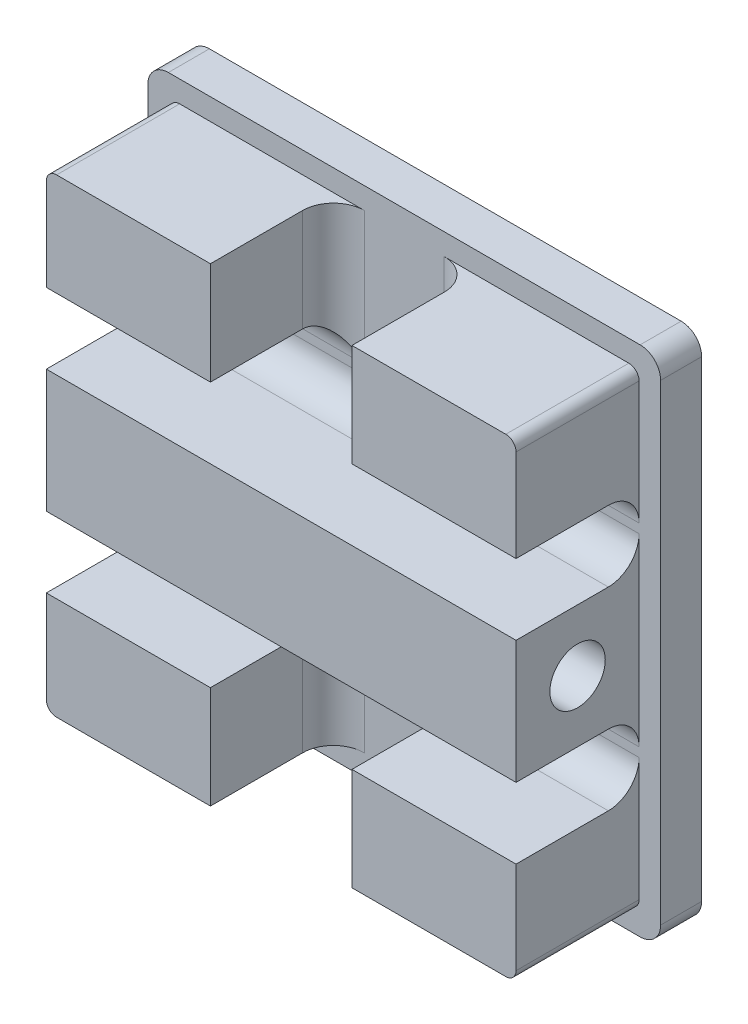
SolidWorks part; units mm, degrees
material "PLA"
ref_plane "前视基准面" through (0, 0, 0) normal (0, 0, 1) x (1, 0, 0)
ref_plane "上视基准面" through (0, 0, 0) normal (0, 1, 0) x (1, 0, 0)
ref_plane "右视基准面" through (0, 0, 0) normal (1, 0, 0) x (0, 0, -1)
sketch "草图1" plane through (0, 0, 0) normal (0, 0, 1) x (1, 0, 0)
  line L1 (12.5, -12.5) -> (-12.5, -12.5)
  line L2 (12.5, -12.5) -> (12.5, 12.5)
  line L3 (12.5, 12.5) -> (-12.5, 12.5)
  line L4 (-12.5, -12.5) -> (-12.5, 12.5)
  line L5 (12.5, -12.5) -> (-12.5, 12.5) construction
  line L6 (12.5, 12.5) -> (-12.5, -12.5) construction
  point P0 (0, 0)
  dimension "D1" = 25
extrude "凸台-拉伸1" add sketch "草图1" along normal blind 2
sketch "草图2" plane through (0, 0, 2) normal (0, 0, 1) x (1, 0, 0)
  line L1 (-11.45, 11.45) -> (11.45, 11.45)
  line L2 (-11.45, 11.45) -> (-11.45, -11.45)
  line L3 (-11.45, -11.45) -> (11.45, -11.45)
  line L4 (11.45, 11.45) -> (11.45, -11.45)
  line L5 (-11.45, 11.45) -> (11.45, -11.45) construction
  line L6 (-11.45, -11.45) -> (11.45, 11.45) construction
  point P0 (0, 0)
  dimension "D1" = 22.9
extrude "凸台-拉伸2" add sketch "草图2" along normal blind 6
fillet "圆角1" radius 1 4 edges at (-12.5, 12.5, 1) (-12.5, -12.5, 1) (12.5, -12.5, 1) (12.5, 12.5, 1)
sketch "草图6" plane through (0, 0, 0) normal (0, 0, -1) x (-1, 0, 0)
  line L0 (-7.682, -0.682) -> (0, -8.364)
  line L1 (0, -8.364) -> (7.682, -0.682)
  line L2 (-4.5, 2.5) -> (4.5, 2.5) construction
  line L3 (0, 0) -> (0, 2.5) construction
  arc A0 (0, 2.5) -> (-7.682, -0.682) centre (-4.5, 2.5) ccw
  arc A1 (7.682, -0.682) -> (0, 2.5) centre (4.5, 2.5) ccw
  dimension "D1" = 4.5
  dimension "D2" = 90
  dimension "D3" = 2.5
extrude "切除-拉伸3" cut sketch "草图6" against normal blind 0.6
fillet "圆角2" radius 0.5 4 edges at (-11.45, -11.45, 5) (11.45, -11.45, 5) (11.45, 11.45, 5) (-11.45, 11.45, 5)
fillet "圆角3" radius 0.1 1 edges at (0, 2.5, 0.3)
sketch "草图7" plane through (11.45, 0, 0) normal (1, 0, 0) x (0, 0, -1)
  line L0 (-2, -10.95) -> (-2, 10.95) construction
  circle A0 centre (-5, 0) radius 1.35
  dimension "D2" = 2.7
  dimension "D1" = 3
extrude "切除-拉伸4" cut sketch "草图7" against normal through all
sketch "草图8" plane through (0, 0, 8) normal (0, 0, 1) x (1, 0, 0)
  line L0 (11.45, -10.95) -> (11.45, 10.95) construction
  line L1 (-11.45, 3) -> (11.45, 3)
  line L2 (-11.45, 3) -> (-11.45, 6.45)
  line L3 (-11.45, 6.45) -> (-3.45, 6.45)
  line L4 (11.45, 3) -> (11.45, 6.45)
  line L5 (-11.45, 3) -> (11.45, 6.45) construction
  line L6 (-11.45, 6.45) -> (11.45, 3) construction
  line L7 (10.95, 11.45) -> (-10.95, 11.45) construction
  line L8 (0, 0) -> (2.9118, 0) construction
  line L9 (-11.45, 10.95) -> (-11.45, -10.95) construction
  line L10 (-11.45, -6.45) -> (-3.45, -6.45)
  line L11 (11.45, -3) -> (11.45, -6.45)
  line L12 (-11.45, -3) -> (11.45, -3)
  line L13 (-11.45, -3) -> (-11.45, -6.45)
  line L14 (3.45, 11.45) -> (3.45, 6.45)
  line L15 (0, 0) -> (0, 3) construction
  line L16 (-3.45, 11.45) -> (-3.45, 6.45)
  line L17 (-3.45, -11.45) -> (-3.45, -6.45)
  line L18 (3.45, -11.45) -> (3.45, -6.45)
  line L19 (11.45, -10.95) -> (11.45, 10.95) construction
  line L20 (3.45, 11.45) -> (-3.45, 11.45)
  line L21 (3.45, -11.45) -> (-3.45, -11.45)
  line L22 (3.45, 6.45) -> (11.45, 6.45)
  line L23 (3.45, -6.45) -> (11.45, -6.45)
  point P0 (0, 4.725)
  dimension "D1" = 5
  dimension "D2" = 6
  dimension "D3" = 8
extrude "切除-拉伸5" cut sketch "草图8" against normal up to surface (6 mm away) up to face at (0, 0, 2)
fillet "圆角4" radius 1.5 10 edges at (0, -3, 2) (0, 3, 2) (-3.45, 8.95, 2) (-7.45, 6.45, 2) (-3.45, -8.95, 2) (-7.45, -6.45, 2) (7.45, -6.45, 2) (3.45, -8.95, 2) (7.45, 6.45, 2) (3.45, 8.95, 2)
